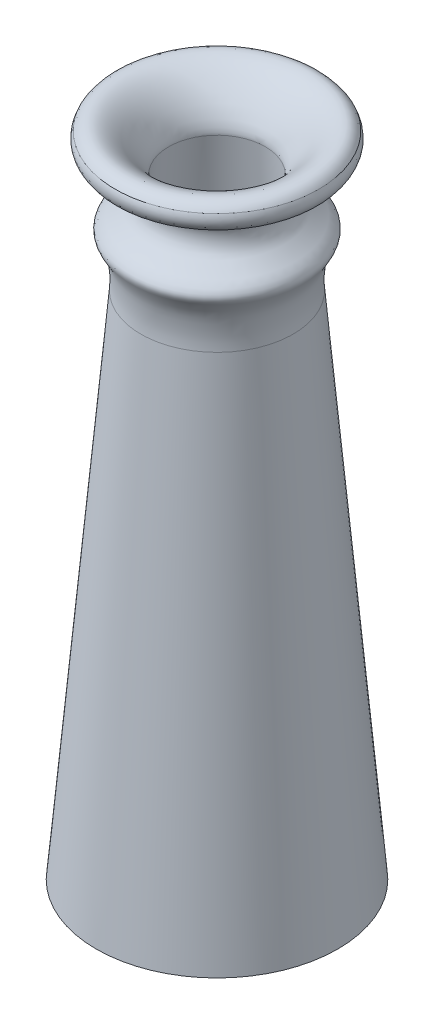
SolidWorks part; units mm, degrees
ref_plane "Front Plane" through (0, 0, 0) normal (0, 0, 1) x (1, 0, 0)
ref_plane "Top Plane" through (0, 0, 0) normal (0, 1, 0) x (1, 0, 0)
ref_plane "Right Plane" through (0, 0, 0) normal (1, 0, 0) x (0, 0, -1)
sketch "Sketch1" plane through (0, 0, 0) normal (0, 0, 1) x (1, 0, 0)
  line L0 (0, 0) -> (-26.665, 0) construction
  line L1 (0, 0) -> (0, 903.7082) construction
  line L2 (-14.6668, 165) -> (-26.6668, 170) construction
  line L3 (-26.665, 0) -> (-12.6668, 160)
  line L4 (-26.6668, 165) -> (-14.6668, 165) construction
  line L5 (-26.6668, 170) -> (-26.6668, 165) construction
  line L6 (-14.6668, 165) -> (-12.6668, 160) construction
  line L7 (-14.6668, 160) -> (-14.6668, 165) construction
  line L8 (-14.6668, 160) -> (-12.6668, 160) construction
  line L9 (-26.1811, 165.9418) -> (-17.9593, 161.1065)
  line L10 (-19.9628, 133.757) -> (-31.665, 0)
  line L11 (-31.665, 0) -> (-26.665, 0)
  spline S0 degree 3 poles (-12.6668, 160) (-12.3061, 164.1234) (-22.5938, 176.1384) (-26.6668, 170) knots 0 0 0 0 1 1 1 1
  spline S1 degree 3 poles (-17.9593, 161.1065) (-15.2948, 159.9232) (-15.4745, 153.7423) (-20.4175, 151.4327) (-23.7525, 147.8153) (-20.5487, 143.9424) (-19.8861, 138.7975) (-19.7664, 136.0012) (-19.9628, 133.757) knots 0 0 0 0 0.24713 0.423699 0.532204 0.643267 0.840065 1 1 1 1
  spline S2 degree 2 poles (-26.6668, 170) (-27.7544, 167.8217) (-26.1811, 165.9418) knots 0 0 0 1 1 1
  point P12 (-16.7821, 154.1902)
  point P13 (-17.9593, 161.1065)
  dimension "D1" = 26.665
  dimension "D2" = 160
  dimension "D3" = 5
  dimension "D4" = 12
  dimension "D5" = 2
  dimension "D6" = 5
  dimension "D7" = 85
  dimension "D8" = 5
revolve "Revolve1" add sketch "Sketch1" angle 360 about L1
